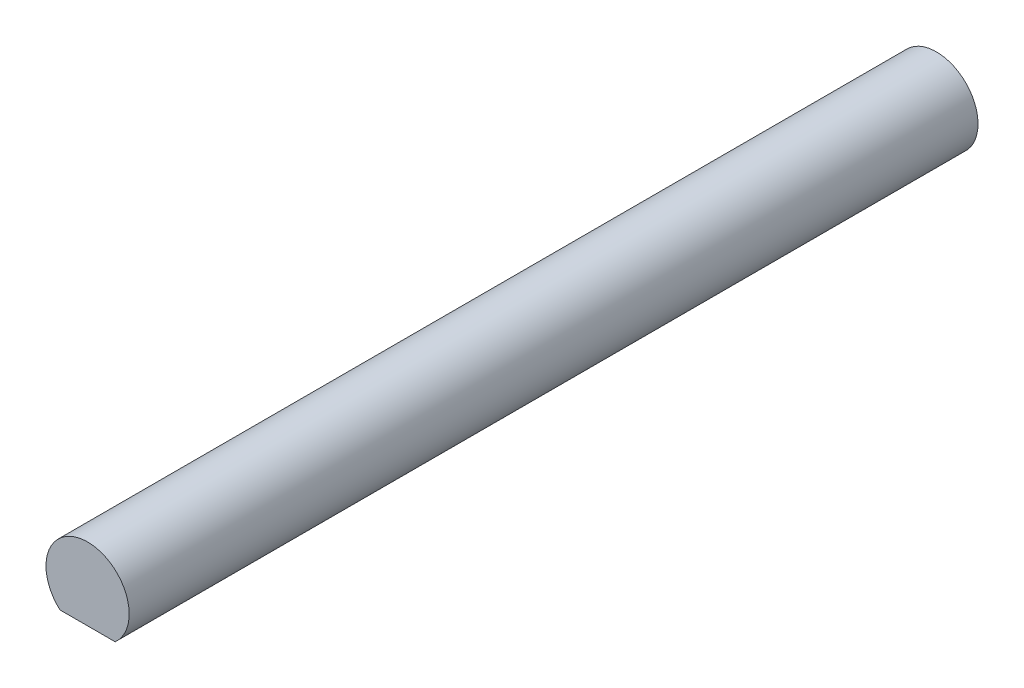
SolidWorks part; units mm, degrees
ref_plane "Front Plane" through (0, 0, 0) normal (0, 0, 1) x (1, 0, 0)
ref_plane "Top Plane" through (0, 0, 0) normal (0, 1, 0) x (1, 0, 0)
ref_plane "Right Plane" through (0, 0, 0) normal (1, 0, 0) x (0, 0, -1)
sketch "Sketch1" plane through (0, 0, 0) normal (0, 0, 1) x (1, 0, 0)
  line L0 (-0.9751, -1.1) -> (0.9751, -1.1)
  arc A0 (0.9751, -1.1) -> (-0.9751, -1.1) centre (0, 0) ccw
  dimension "D1" = 2.94
  dimension "D2" = 1.1
extrude "Boss-Extrude1" add sketch "Sketch1" along normal blind 30
